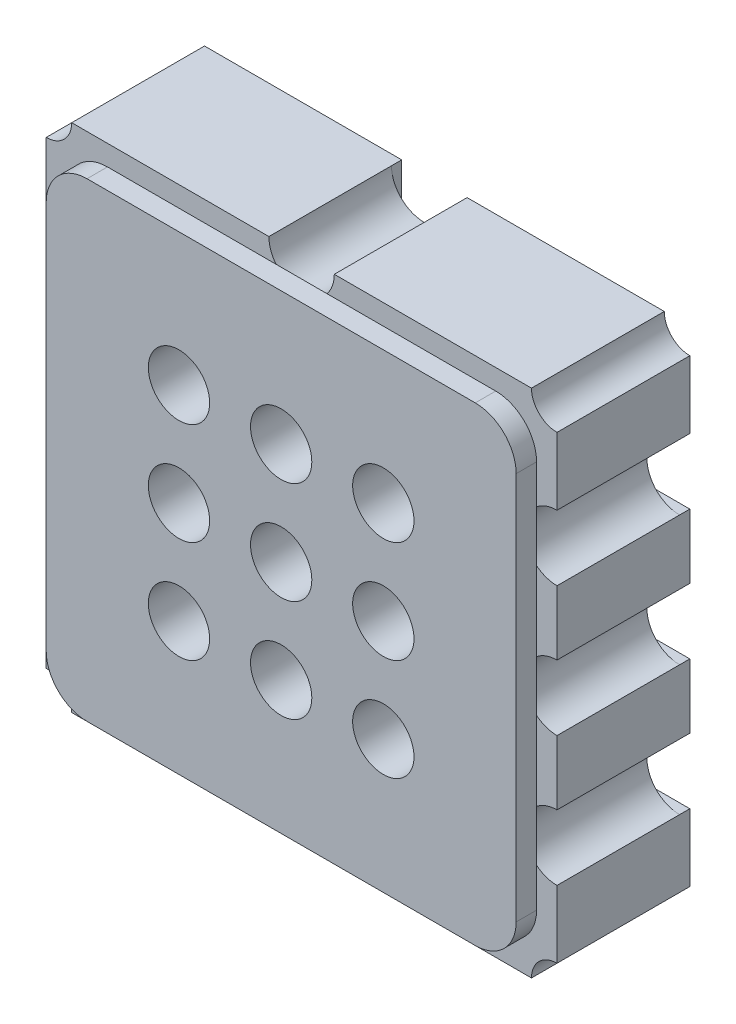
SolidWorks part; units mm, degrees
ref_plane "Спереди" through (0, 0, 0) normal (0, 0, 1) x (1, 0, 0)
ref_plane "Сверху" through (0, 0, 0) normal (0, 1, 0) x (1, 0, 0)
ref_plane "Справа" through (0, 0, 0) normal (1, 0, 0) x (0, 0, -1)
sketch "Эскиз1" plane through (0, 0, 0) normal (0, 0, 1) x (1, 0, 0)
  line L1 (2.5, -2.5) -> (-2.5, -2.5)
  line L2 (2.5, -2.5) -> (2.5, 2.5)
  line L3 (2.5, 2.5) -> (-2.5, 2.5)
  line L4 (-2.5, -2.5) -> (-2.5, 2.5)
  line L5 (2.5, -2.5) -> (-2.5, 2.5) construction
  line L6 (2.5, 2.5) -> (-2.5, -2.5) construction
  point P0 (0, 0)
  dimension "D1" = 5
  dimension "D2" = 5
extrude "Бобышка-Вытянуть1" add sketch "Эскиз1" along normal blind 1.3
sketch "Эскиз2" plane through (0, 0, 1.3) normal (0, 0, 1) x (1, 0, 0)
  line L0 (-2.5, 2.5) -> (-2.5, -2.5) construction
  line L1 (2.3, -2.3) -> (-2.3, -2.3)
  line L2 (2.3, -2.3) -> (2.3, 2.3)
  line L3 (2.3, 2.3) -> (-2.3, 2.3)
  line L4 (-2.3, -2.3) -> (-2.3, 2.3)
  line L5 (2.3, -2.3) -> (-2.3, 2.3) construction
  line L6 (2.3, 2.3) -> (-2.3, -2.3) construction
  line L7 (2.5, 2.5) -> (-2.5, 2.5) construction
  point P0 (0, 0)
  dimension "D1" = 0.2
  dimension "D2" = 0.2
extrude "Бобышка-Вытянуть2" add sketch "Эскиз2" along normal blind 0.2
sketch "Эскиз3" plane through (0, 0, 1.5) normal (0, 0, 1) x (1, 0, 0)
  line L0 (0, 0) -> (1, 0) construction
  line L1 (0, 0) -> (-1, 0) construction
  line L2 (0, -1) -> (1, -1) construction
  line L3 (0, -1) -> (-1, -1) construction
  circle A0 centre (0, 0) radius 0.3
  circle A1 centre (1, 0) radius 0.3
  circle A2 centre (1, 1) radius 0.3
  circle A3 centre (0, 1) radius 0.3
  circle A4 centre (-1, 0) radius 0.3
  circle A5 centre (-1, 1) radius 0.3
  circle A6 centre (0, -1) radius 0.3
  circle A7 centre (1, -1) radius 0.3
  circle A8 centre (-1, -1) radius 0.3
  point P29 (-1.178, -1.4116)
  dimension "D1" = 0.6
  dimension "D4" = 1
  dimension "D6" = 1
  dimension "D8" = 1
  dimension "D9" = 1
  dimension "D2" = 2
  dimension "D3" = 2
  dimension "D5" = 2
  dimension "D7" = 2
extrude "Вырез-Вытянуть2" cut sketch "Эскиз3" against normal blind 0.6
sketch "Эскиз4" plane through (0, 0, 0) normal (0, 0, -1) x (-1, 0, 0)
  line L0 (-2.5, -2.5) -> (-2.5, 2.5) construction
  line L1 (-2.5, 2.5) -> (2.5, 2.5) construction
  line L2 (2.5, -2.5) -> (-2.5, -2.5) construction
  circle A0 centre (-2.5, 0) radius 0.32
  circle A1 centre (2.5, 0) radius 0.32
  circle A2 centre (2.5, 1.27) radius 0.32
  circle A3 centre (-2.5, 1.27) radius 0.32
  circle A4 centre (-2.5, -1.27) radius 0.32
  circle A5 centre (2.5, -1.27) radius 0.32
  circle A6 centre (0, 2.5) radius 0.32
  circle A7 centre (0, -2.5) radius 0.32
  dimension "D1" = 0.64
  dimension "D4" = 5
  dimension "D2" = 2
  dimension "D3" = 2
  dimension "D5" = 2
extrude "Вырез-Вытянуть3" cut sketch "Эскиз4" against normal up to surface (1.3 mm away) up to face at (0, 0, 1.3)
sketch "Эскиз5" plane through (0, 0, 0) normal (0, 0, -1) x (-1, 0, 0)
  circle A0 centre (-2.5, 2.5) radius 0.25
  circle A1 centre (2.5, 2.5) radius 0.25
  circle A2 centre (2.5, -2.5) radius 0.25
  circle A3 centre (-2.5, -2.5) radius 0.25
  dimension "D1" = 0.5
extrude "Вырез-Вытянуть4" cut sketch "Эскиз5" against normal through all
fillet "Скругление1" radius 0.4 4 edges at (-2.3, 2.3, 1.4) (-2.3, -2.3, 1.4) (2.3, 2.3, 1.4) (2.3, -2.3, 1.4)
sketch "Эскиз8" plane through (0, 0, 0) normal (0, 0, -1) x (-1, 0, 0)
  line L0 (-2.5, -0.95) -> (-2.5, -0.32) construction
  line L1 (-2.5, 1.59) -> (-1.33, 1.59)
  line L2 (-2.5, 1.59) -> (-2.5, 0.95)
  line L3 (-2.5, 0.95) -> (-1.33, 0.95)
  line L4 (-1.33, 1.59) -> (-1.33, 0.95)
  line L5 (-2.5, 0.32) -> (-1.33, 0.32)
  line L6 (-2.5, 0.32) -> (-2.5, -0.32)
  line L7 (-2.5, -0.32) -> (-1.33, -0.32)
  line L8 (-1.33, 0.32) -> (-1.33, -0.32)
  line L9 (-2.5, -0.95) -> (-1.33, -0.95)
  line L10 (-2.5, -0.95) -> (-2.5, -1.59)
  line L11 (-2.5, -1.59) -> (-1.33, -1.59)
  line L12 (-1.33, -0.95) -> (-1.33, -1.59)
  line L13 (-2.25, 2.5) -> (-0.32, 2.5) construction
  line L14 (2.5, -1.59) -> (1.33, -1.59)
  line L15 (2.5, -1.59) -> (2.5, -0.95)
  line L16 (2.5, -0.95) -> (1.33, -0.95)
  line L17 (1.33, -1.59) -> (1.33, -0.95)
  line L18 (2.5, -0.32) -> (1.33, -0.32)
  line L19 (2.5, -0.32) -> (2.5, 0.32)
  line L20 (2.5, 0.32) -> (1.33, 0.32)
  line L21 (1.33, -0.32) -> (1.33, 0.32)
  line L22 (2.5, 0.95) -> (1.33, 0.95)
  line L23 (2.5, 0.95) -> (2.5, 1.59)
  line L24 (2.5, 1.59) -> (1.33, 1.59)
  line L25 (1.33, 0.95) -> (1.33, 1.59)
  line L26 (-0.32, -2.5) -> (0.32, -2.5)
  line L27 (-0.32, -2.5) -> (-0.32, -1.27)
  line L28 (-0.32, -1.27) -> (0.32, -1.27)
  line L29 (0.32, -2.5) -> (0.32, -1.27)
  line L30 (-0.32, 2.5) -> (0.32, 2.5)
  line L31 (-0.32, 2.5) -> (-0.32, 0.42)
  line L32 (-0.32, 0.42) -> (0.32, 0.42)
  line L33 (0.32, 2.5) -> (0.32, 0.42)
  arc A0 (-2.5, -1.59) -> (-2.5, -0.95) centre (-2.5, -1.27) ccw construction
  arc A1 (2.5, 1.59) -> (2.5, 0.95) centre (2.5, 1.27) ccw construction
  arc A2 (-0.32, 2.5) -> (0.32, 2.5) centre (0, 2.5) ccw construction
  dimension "D1" = 1.17
  dimension "D2" = 0.64
  dimension "D3" = 1.23
  dimension "D4" = 2.08
extrude "Вырез-Вытянуть5" cut sketch "Эскиз8" against normal blind 0.1
